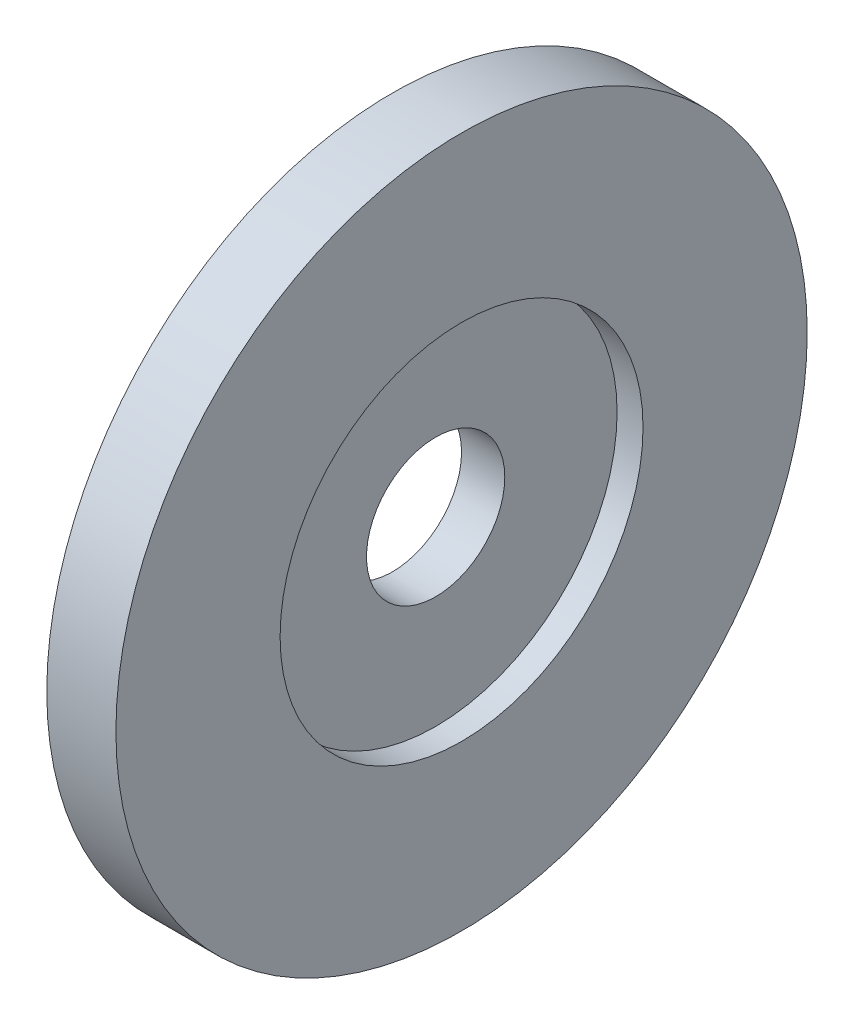
SolidWorks part; units mm, degrees
ref_plane "Alzado" through (0, 0, 0) normal (0, 0, 1) x (1, 0, 0)
ref_plane "Planta" through (0, 0, 0) normal (0, 1, 0) x (1, 0, 0)
ref_plane "Vista lateral" through (0, 0, 0) normal (1, 0, 0) x (0, 0, -1)
sketch "Croquis1" plane through (0, 0, 0) normal (1, 0, 0) x (0, 0, -1)
  line L0 (0, 0) -> (-4.1, 0) construction
  line L3 (-66, 0) -> (-98.2419, 0) construction
  circle A0 centre (-70, 0) radius 20
  circle A2 centre (-70, 0) radius 4
  dimension "D1" = 40
  dimension "D4" = 70
  dimension "D5" = 8
extrude "Saliente-Extruir1" add sketch "Croquis1" along normal blind 4
sketch "Croquis2" plane through (4, 0, 0) normal (1, 0, 0) x (0, 0, -1)
  circle A0 centre (-70, 0) radius 10.5
  dimension "D1" = 21
extrude "Cortar-Extruir1" cut sketch "Croquis2" against normal blind 1.5
